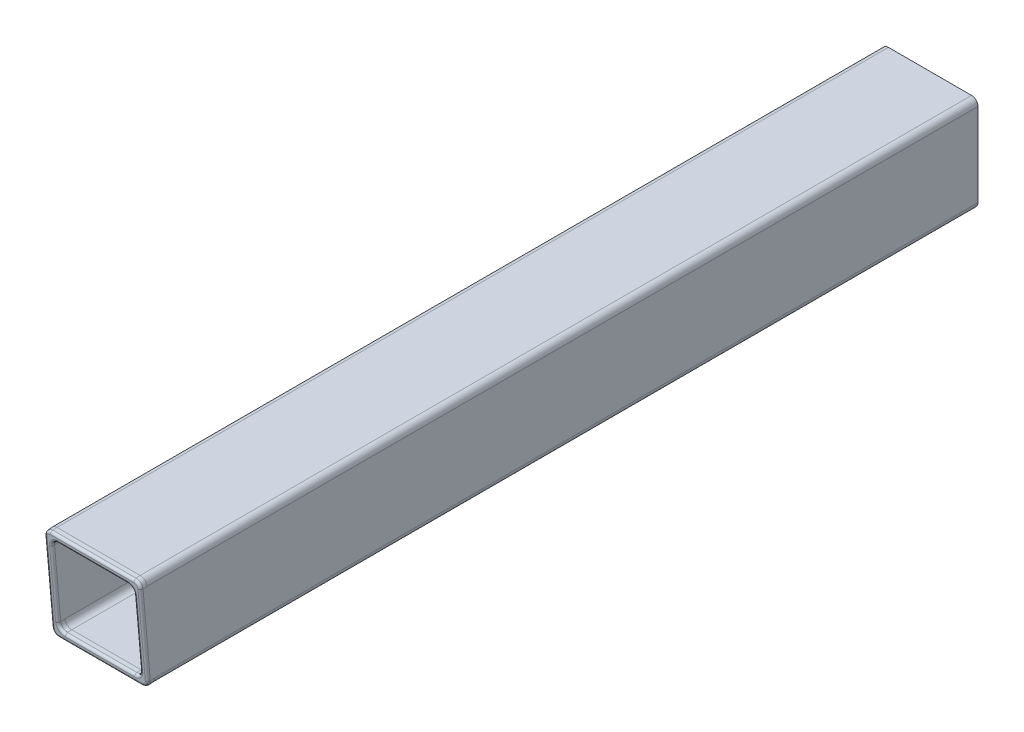
SolidWorks part; units mm, degrees
material "ASTM A500 Grade B Steel"
ref_plane "Front Plane" through (0, 0, 0) normal (0, 0, 1) x (1, 0, 0)
ref_plane "Top Plane" through (0, 0, 0) normal (0, 1, 0) x (1, 0, 0)
ref_plane "Right Plane" through (0, 0, 0) normal (1, 0, 0) x (0, 0, -1)
sketch "Sketch1" plane through (0, 0, 0) normal (0, 0, 1) x (1, 0, 0)
  line L0 (5.3086, -2.7686) -> (32.7914, -2.7686)
  line L1 (2.54, 0) -> (35.56, 0)
  line L2 (0, -2.54) -> (0, -35.56)
  line L3 (2.54, -38.1) -> (35.56, -38.1)
  line L4 (38.1, -2.54) -> (38.1, -35.56)
  line L5 (35.3314, -5.3086) -> (35.3314, -32.7914)
  line L6 (5.3086, -35.3314) -> (32.7914, -35.3314)
  line L7 (2.7686, -5.3086) -> (2.7686, -32.7914)
  line L8 (0, 0) -> (0, -38.1) construction
  line L9 (0, -38.1) -> (38.1, -38.1) construction
  line L10 (38.1, 0) -> (38.1, -38.1) construction
  line L11 (2.7686, -2.7686) -> (2.7686, -35.3314) construction
  line L12 (2.7686, -35.3314) -> (35.3314, -35.3314) construction
  line L13 (35.3314, -2.7686) -> (35.3314, -35.3314) construction
  line L14 (2.7686, -2.7686) -> (35.3314, -2.7686) construction
  line L15 (0, 0) -> (38.1, 0) construction
  arc A0 (0, -35.56) -> (2.54, -38.1) centre (2.54, -35.56) ccw
  arc A1 (38.1, -35.56) -> (35.56, -38.1) centre (35.56, -35.56) cw
  arc A2 (2.7686, -32.7914) -> (5.3086, -35.3314) centre (5.3086, -32.7914) ccw
  arc A3 (32.7914, -35.3314) -> (35.3314, -32.7914) centre (32.7914, -32.7914) ccw
  arc A4 (35.3314, -5.3086) -> (32.7914, -2.7686) centre (32.7914, -5.3086) ccw
  arc A5 (38.1, -2.54) -> (35.56, 0) centre (35.56, -2.54) ccw
  arc A6 (0, -2.54) -> (2.54, 0) centre (2.54, -2.54) cw
  arc A7 (5.3086, -2.7686) -> (2.7686, -5.3086) centre (5.3086, -5.3086) ccw
  point P12 (0, -38.1)
  dimension "D4" = 2.54
  dimension "D3" = 2.7686
extrude "Boss-Extrude1" add sketch "Sketch1" along normal blind 330
sketch "Sketch2" plane through (38.1, 0, 0) normal (1, 0, 0) x (0, 0, -1)
  line L0 (-330, 0) -> (-326.6667, -38.1)
  line L1 (-330, -38.1) -> (0, -38.1) construction
  line L5 (-330, 0) -> (-330, -38.1)
  line L6 (-326.6667, -38.1) -> (-330, -38.1)
  dimension "D1" = 5
extrude "Cut-Extrude1" cut sketch "Sketch2" against normal through all
sketch "Sketch3" plane through (0, -28.6519, 327.4933) normal (0, -0.0872, 0.9962) x (1, 0, 0)
  line L0 (35.3314, 23.4325) -> (35.3314, -4.1553) construction
  line L1 (32.7914, -6.705) -> (5.3086, -6.705) construction
  line L2 (2.7686, -4.1553) -> (2.7686, 23.4325) construction
  line L3 (5.3086, 25.9822) -> (32.7914, 25.9822) construction
  line L4 (2.54, -9.4841) -> (35.56, -9.4841)
  line L5 (38.1, -6.9344) -> (38.1, 26.2117)
  line L6 (35.56, 28.7614) -> (2.54, 28.7614)
  line L7 (0, 26.2117) -> (0, -6.9344)
  line L8 (2.54, -9.4841) -> (35.56, -9.4841)
  line L9 (38.1, -6.9344) -> (38.1, 26.2117)
  line L10 (35.56, 28.7614) -> (2.54, 28.7614)
  line L11 (0, 26.2117) -> (0, -6.9344)
  line L12 (35.3314, 23.4325) -> (35.3314, -4.1553)
  line L13 (32.7914, -6.705) -> (5.3086, -6.705)
  line L14 (2.7686, -4.1553) -> (2.7686, 23.4325)
  line L15 (5.3086, 25.9822) -> (32.7914, 25.9822)
  ellipse E0 centre (32.7914, 23.4325) end of major axis (32.7914, 20.8828) minor radius 2.54 (35.3314, 23.4325) -> (32.7914, 25.9822) ccw construction
  ellipse E1 centre (32.7914, -4.1553) end of major axis (32.7914, -1.6056) minor radius 2.54 (32.7914, -6.705) -> (35.3314, -4.1553) ccw construction
  ellipse E2 centre (5.3086, -4.1553) end of major axis (5.3086, -1.6056) minor radius 2.54 (2.7686, -4.1553) -> (5.3086, -6.705) ccw construction
  ellipse E3 centre (5.3086, 23.4325) end of major axis (5.3086, 20.8828) minor radius 2.54 (5.3086, 25.9822) -> (2.7686, 23.4325) ccw construction
  ellipse E4 centre (35.56, -6.9344) end of major axis (35.56, -9.4841) minor radius 2.54 (35.56, -9.4841) -> (38.1, -6.9344) ccw
  ellipse E5 centre (35.56, 26.2117) end of major axis (35.56, 23.662) minor radius 2.54 (38.1, 26.2117) -> (35.56, 28.7614) ccw
  ellipse E6 centre (2.54, 26.2117) end of major axis (2.54, 23.662) minor radius 2.54 (2.54, 28.7614) -> (0, 26.2117) ccw
  ellipse E7 centre (2.54, -6.9344) end of major axis (2.54, -9.4841) minor radius 2.54 (0, -6.9344) -> (2.54, -9.4841) ccw
  ellipse E8 centre (35.56, -6.9344) end of major axis (35.56, -9.4841) minor radius 2.54 (35.56, -9.4841) -> (38.1, -6.9344) ccw
  ellipse E9 centre (35.56, 26.2117) end of major axis (35.56, 23.662) minor radius 2.54 (38.1, 26.2117) -> (35.56, 28.7614) ccw
  ellipse E10 centre (2.54, 26.2117) end of major axis (2.54, 23.662) minor radius 2.54 (2.54, 28.7614) -> (0, 26.2117) ccw
  ellipse E11 centre (2.54, -6.9344) end of major axis (2.54, -9.4841) minor radius 2.54 (0, -6.9344) -> (2.54, -9.4841) ccw
  ellipse E12 centre (32.7914, 23.4325) end of major axis (32.7914, 20.8828) minor radius 2.54 (35.3314, 23.4325) -> (32.7914, 25.9822) ccw
  ellipse E13 centre (32.7914, -4.1553) end of major axis (32.7914, -6.705) minor radius 2.54 (32.7914, -6.705) -> (35.3314, -4.1553) ccw
  ellipse E14 centre (5.3086, -4.1553) end of major axis (5.3086, -6.705) minor radius 2.54 (2.7686, -4.1553) -> (5.3086, -6.705) ccw
  ellipse E15 centre (5.3086, 23.4325) end of major axis (5.3086, 20.8828) minor radius 2.54 (5.3086, 25.9822) -> (2.7686, 23.4325) ccw
  dimension "D1" = 0
extrude "Boss-Extrude2" add sketch "Sketch3" along normal up to surface (2.6153 mm away)
fillet "Fillet1" radius 1 16 edges at (0.7439, -0.9719, 332.5403) (19.05, -0.2279, 332.6054) (37.3561, -0.9719, 332.5403) (38.1, -19.2779, 330.9387) (37.3561, -37.584, 329.3372) (19.05, -38.3279, 329.2721) (0.7439, -37.584, 329.3372) (0, -19.2779, 330.9387) (19.05, -2.9965, 332.3632) (3.5125, -3.7405, 332.2981) (2.7686, -19.2779, 330.9387) (3.5125, -34.8154, 329.5794) (19.05, -35.5593, 329.5143) (34.5875, -34.8154, 329.5794) (35.3314, -19.2779, 330.9387) (34.5875, -3.7405, 332.2981)
